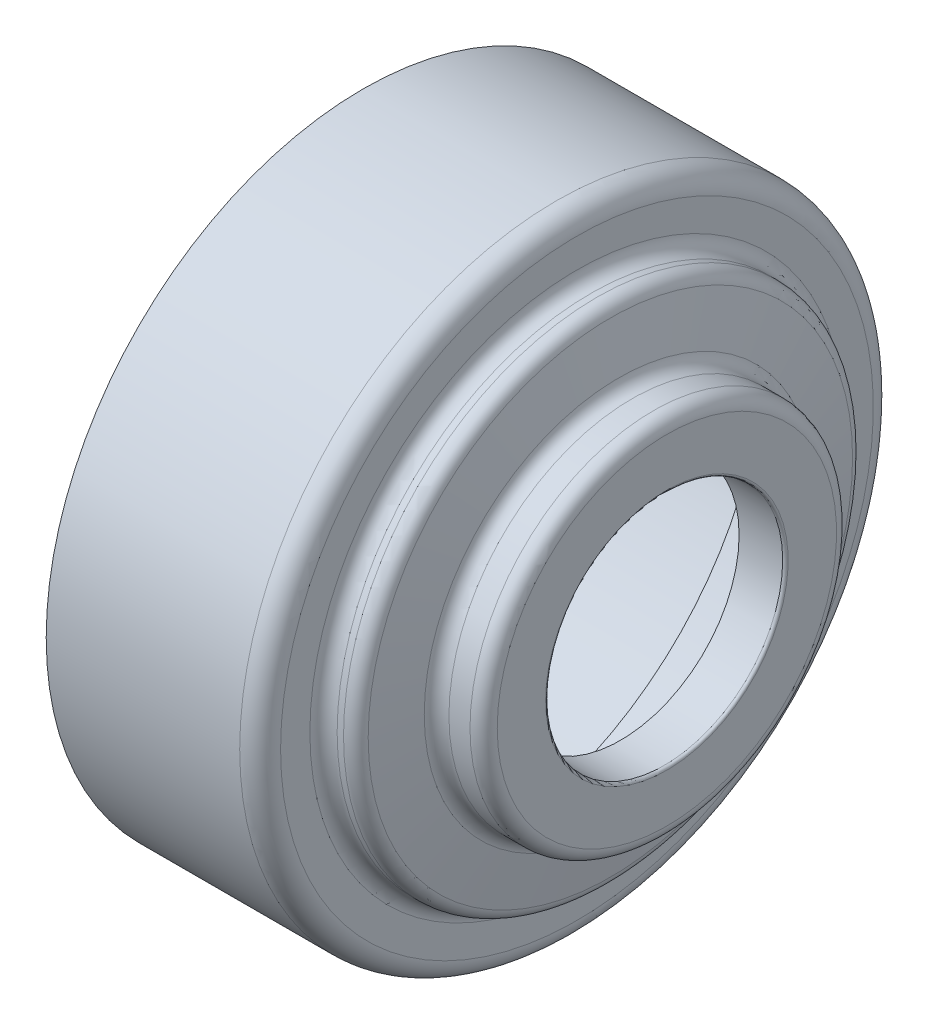
SolidWorks part; units mm, degrees
ref_plane "前视基准面" through (0, 0, 0) normal (0, 0, 1) x (1, 0, 0)
ref_plane "上视基准面" through (0, 0, 0) normal (0, 1, 0) x (1, 0, 0)
ref_plane "右视基准面" through (0, 0, 0) normal (1, 0, 0) x (0, 0, -1)
sketch "草图2" plane through (0, 0, 0) normal (0, 0, 1) x (1, 0, 0)
  line L0 (-36.9366, 0) -> (44.5849, 0) construction
  line L1 (0, 36.0368) -> (0, -37.1166) construction
  line L2 (-14.5, 22) -> (-6.5, 22)
  line L3 (-6.5, 22) -> (-6.5, 21.4)
  line L4 (-6.5, 21.4) -> (0, 21.4)
  line L5 (0, 21.4) -> (0, 17.4)
  line L6 (0, 17.4) -> (2.5, 17.4)
  line L8 (3.4081, 12.25) -> (6.6, 12.25)
  line L9 (6.6, 12.25) -> (6.6, 9.4)
  line L10 (6.6, 9.4) -> (4.4, 9.4)
  line L11 (4.4, 9.4) -> (4.4, 8.7)
  line L12 (4.4, 8.7) -> (7.8, 8.7)
  line L13 (-14.5, 22) -> (-14.5, 23.25)
  line L14 (-14.5, 23.25) -> (1.2, 23.25)
  line L15 (1.2, 23.25) -> (1.2, 18.6)
  line L16 (1.2, 18.6) -> (3.5069, 18.6)
  line L18 (4.415, 13.45) -> (7.8, 13.45)
  line L19 (7.8, 13.45) -> (7.8, 8.7)
  line L20 (2.5, 17.4) -> (3.4081, 12.25)
  line L21 (3.5069, 18.6) -> (4.415, 13.45)
  dimension "D1" = 44
  dimension "D2" = 0.6
  dimension "D3" = 8
  dimension "D4" = 14.5
  dimension "D5" = 34.8
  dimension "D6" = 2.5
  dimension "D7" = 18.8
  dimension "D8" = 0.7
  dimension "D9" = 4.4
  dimension "D10" = 2.2
  dimension "D11" = 24.5
  dimension "D12" = 1.85
  dimension "D13" = 46.5
  dimension "D14" = 1.2
  dimension "D15" = 10
  dimension "D16" = 1.2
  dimension "D17" = 1.2
  dimension "D18" = 1.2
  dimension "D19" = 1.2
revolve "旋转1" add sketch "草图2" angle 360 about L0
fillet "圆角1" radius 0.2 5 edges at (0, 0, 17.4) (0, 0, 21.4) (7.8, 0, 8.7) (6.6, 0, 12.25) (2.5, 0, 17.4)
fillet "圆角2" radius 1 4 edges at (1.2, 0, 18.6) (7.8, 0, 13.45) (3.5069, 0, 18.6) (4.415, 0, 13.45)
fillet "圆角3" radius 1.5 2 edges at (1.2, 0, 23.25) (3.4081, 0, 12.25)
